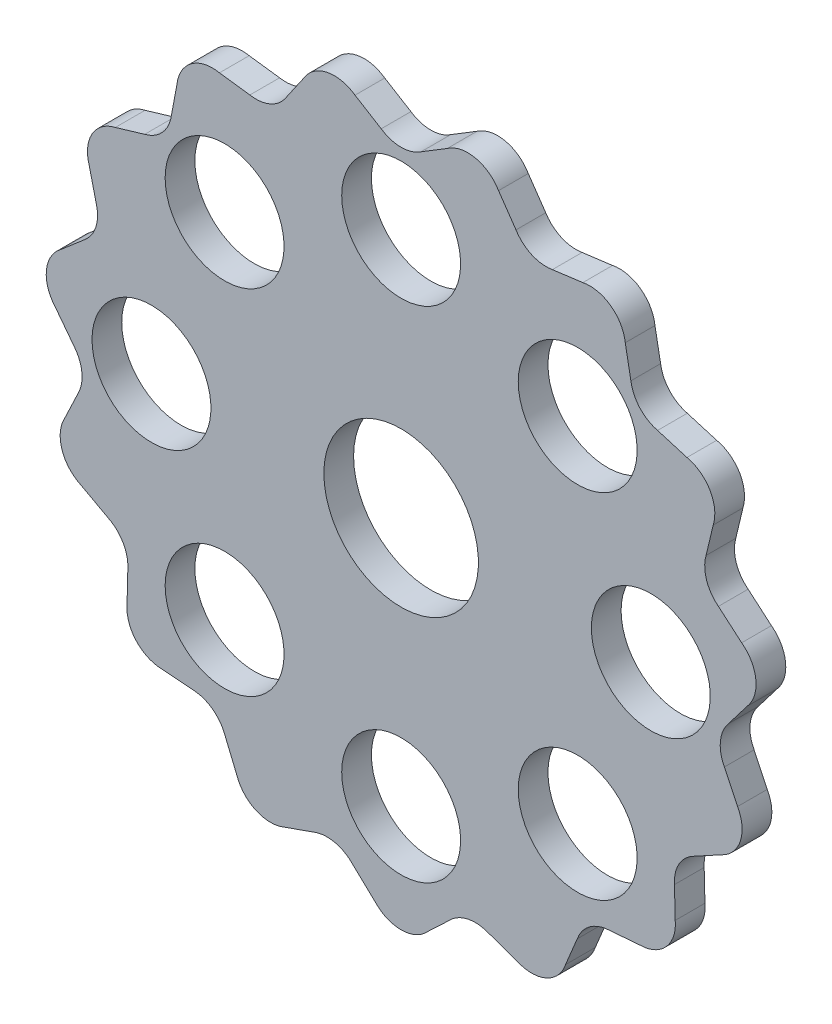
SolidWorks part; units mm, degrees
ref_plane "Plan de face" through (0, 0, 0) normal (0, 0, 1) x (1, 0, 0)
ref_plane "Plan de dessus" through (0, 0, 0) normal (0, 1, 0) x (1, 0, 0)
ref_plane "Plan de droite" through (0, 0, 0) normal (1, 0, 0) x (0, 0, -1)
sketch "Esquisse1" plane through (0, 0, 0) normal (0, 0, 1) x (1, 0, 0)
  line L0 (0, 0) -> (0, 70.8269) construction
  line L1 (0, 0) -> (-16.4135, 77.2197) construction
  line L2 (0, 0) -> (12.0589, 56.7326) construction
  line L3 (-3.3535, 55.0246) -> (3.3535, 55.0246) construction
  line L4 (0, 0) -> (-11.2473, 52.9146) construction
  line L5 (0, 0) -> (12.0589, 56.7326) construction
  line L6 (-11.2272, 52.82) -> (0, 0) construction
  line L7 (0, 0) -> (11.2272, 52.82) construction
  line L8 (-11.2272, 52.82) -> (11.2272, 52.82) construction
  line L9 (-7.7561, 57.7139) -> (7.7561, 57.7139) construction
  line L10 (-7.7561, 57.7139) -> (-3.3535, 55.0246)
  line L11 (3.3535, 55.0246) -> (7.7561, 57.7139)
  line L12 (0, 0) -> (17.0982, 80.4405) construction
  line L13 (16.3889, 55.879) -> (19.317, 51.6315)
  line L14 (25.4441, 48.9035) -> (30.5599, 49.5696)
  line L15 (37.7, 44.382) -> (38.6474, 39.3108)
  line L16 (43.1352, 34.3266) -> (48.0796, 32.8543)
  line L17 (52.4925, 25.211) -> (51.2953, 20.1929)
  line L18 (53.3678, 13.8142) -> (57.286, 10.4581)
  line L19 (58.2085, 1.6808) -> (55.0737, -2.4166)
  line L20 (54.3727, -9.0867) -> (56.5871, -13.7463)
  line L21 (53.8598, -22.14) -> (49.3295, -24.6081)
  line L22 (45.976, -30.4165) -> (46.1037, -35.5739)
  line L23 (40.1982, -42.1327) -> (35.0557, -42.5447)
  line L24 (29.6297, -46.487) -> (27.6486, -51.2505)
  line L25 (19.586, -54.8402) -> (14.7204, -53.125)
  line L26 (8.1601, -54.5194) -> (4.4128, -58.0653)
  line L27 (-4.4128, -58.0653) -> (-8.1601, -54.5194)
  line L28 (-14.7204, -53.125) -> (-19.586, -54.8402)
  line L29 (-27.6486, -51.2505) -> (-29.6297, -46.487)
  line L30 (-35.0557, -42.5447) -> (-40.1982, -42.1327)
  line L31 (-46.1037, -35.5739) -> (-45.976, -30.4165)
  line L32 (-49.3295, -24.6081) -> (-53.8598, -22.14)
  line L33 (-56.5871, -13.7463) -> (-54.3727, -9.0867)
  line L34 (-55.0737, -2.4166) -> (-58.2085, 1.6808)
  line L35 (-57.286, 10.4581) -> (-53.3678, 13.8142)
  line L36 (-51.2953, 20.1929) -> (-52.4925, 25.211)
  line L37 (-48.0796, 32.8543) -> (-43.1352, 34.3266)
  line L38 (-38.6474, 39.3108) -> (-37.7, 44.382)
  line L39 (-30.5599, 49.5696) -> (-25.4441, 48.9035)
  line L40 (-19.317, 51.6315) -> (-16.3889, 55.879)
  circle A4 centre (0, 0) radius 58 construction
  arc A5 (-3.3535, 55.0246) -> (3.3535, 55.0246) centre (0, 60) ccw
  arc A6 (12.4747, 58.6889) -> (7.7561, 57.7139) centre (11.2272, 52.82) ccw
  arc A8 (-12.4747, 58.6889) -> (-7.7561, 57.7139) centre (-11.2272, 52.82) cw
  arc A9 (12.4747, 58.6889) -> (16.3889, 55.879) centre (11.2272, 52.82) cw
  arc A10 (19.317, 51.6315) -> (25.4441, 48.9035) centre (24.4042, 54.8127) ccw
  arc A11 (35.2671, 48.541) -> (30.5599, 49.5696) centre (31.7404, 43.6869) ccw
  arc A12 (35.2671, 48.541) -> (37.7, 44.382) centre (31.7404, 43.6869) cw
  arc A13 (38.6474, 39.3108) -> (43.1352, 34.3266) centre (44.5887, 40.1478) ccw
  arc A14 (51.9615, 30) -> (48.0796, 32.8543) centre (46.7654, 27) ccw
  arc A15 (51.9615, 30) -> (52.4925, 25.211) centre (46.7654, 27) cw
  arc A16 (51.2953, 20.1929) -> (53.3678, 13.8142) centre (57.0634, 18.541) ccw
  arc A17 (59.6713, 6.2717) -> (57.286, 10.4581) centre (53.7042, 5.6445) ccw
  arc A18 (59.6713, 6.2717) -> (58.2085, 1.6808) centre (53.7042, 5.6445) cw
  arc A19 (55.0737, -2.4166) -> (54.3727, -9.0867) centre (59.6713, -6.2717) ccw
  arc A20 (57.0634, -18.541) -> (56.5871, -13.7463) centre (51.3571, -16.6869) ccw
  arc A21 (57.0634, -18.541) -> (53.8598, -22.14) centre (51.3571, -16.6869) cw
  arc A22 (49.3295, -24.6081) -> (45.976, -30.4165) centre (51.9615, -30) ccw
  arc A23 (44.5887, -40.1478) -> (46.1037, -35.5739) centre (40.1298, -36.1331) ccw
  arc A24 (44.5887, -40.1478) -> (40.1982, -42.1327) centre (40.1298, -36.1331) cw
  arc A25 (35.0557, -42.5447) -> (29.6297, -46.487) centre (35.2671, -48.541) ccw
  arc A26 (24.4042, -54.8127) -> (27.6486, -51.2505) centre (21.9638, -49.3315) ccw
  arc A27 (24.4042, -54.8127) -> (19.586, -54.8402) centre (21.9638, -49.3315) cw
  arc A28 (14.7204, -53.125) -> (8.1601, -54.5194) centre (12.4747, -58.6889) ccw
  arc A29 (0, -60) -> (4.4128, -58.0653) centre (0, -54) ccw
  arc A30 (0, -60) -> (-4.4128, -58.0653) centre (0, -54) cw
  arc A31 (-8.1601, -54.5194) -> (-14.7204, -53.125) centre (-12.4747, -58.6889) ccw
  arc A32 (-24.4042, -54.8127) -> (-19.586, -54.8402) centre (-21.9638, -49.3315) ccw
  arc A33 (-24.4042, -54.8127) -> (-27.6486, -51.2505) centre (-21.9638, -49.3315) cw
  arc A34 (-29.6297, -46.487) -> (-35.0557, -42.5447) centre (-35.2671, -48.541) ccw
  arc A35 (-44.5887, -40.1478) -> (-40.1982, -42.1327) centre (-40.1298, -36.1331) ccw
  arc A36 (-44.5887, -40.1478) -> (-46.1037, -35.5739) centre (-40.1298, -36.1331) cw
  arc A37 (-45.976, -30.4165) -> (-49.3295, -24.6081) centre (-51.9615, -30) ccw
  arc A38 (-57.0634, -18.541) -> (-53.8598, -22.14) centre (-51.3571, -16.6869) ccw
  arc A39 (-57.0634, -18.541) -> (-56.5871, -13.7463) centre (-51.3571, -16.6869) cw
  arc A40 (-54.3727, -9.0867) -> (-55.0737, -2.4166) centre (-59.6713, -6.2717) ccw
  arc A41 (-59.6713, 6.2717) -> (-58.2085, 1.6808) centre (-53.7042, 5.6445) ccw
  arc A42 (-59.6713, 6.2717) -> (-57.286, 10.4581) centre (-53.7042, 5.6445) cw
  arc A43 (-53.3678, 13.8142) -> (-51.2953, 20.1929) centre (-57.0634, 18.541) ccw
  arc A44 (-51.9615, 30) -> (-52.4925, 25.211) centre (-46.7654, 27) ccw
  arc A45 (-51.9615, 30) -> (-48.0796, 32.8543) centre (-46.7654, 27) cw
  arc A46 (-43.1352, 34.3266) -> (-38.6474, 39.3108) centre (-44.5887, 40.1478) ccw
  arc A47 (-35.2671, 48.541) -> (-37.7, 44.382) centre (-31.7404, 43.6869) ccw
  arc A48 (-35.2671, 48.541) -> (-30.5599, 49.5696) centre (-31.7404, 43.6869) cw
  arc A49 (-25.4441, 48.9035) -> (-19.317, 51.6315) centre (-24.4042, 54.8127) ccw
  arc A50 (-12.4747, 58.6889) -> (-16.3889, 55.879) centre (-11.2272, 52.82) ccw
  point P145 (0, 0)
  dimension "D2" = 6
  dimension "D3" = 24
  dimension "D5" = 6
  dimension "D7" = 60
  dimension "D8" = 54
  dimension "D11" = 15
  dimension "D14" = 116
  dimension "D4" = 6
  dimension "D6" = 12
  dimension "D10" = 12
  dimension "D9" = 12
extrude "Boss.-Extru.1" add sketch "Esquisse1" along normal blind 5
sketch "Esquisse2" plane through (0, 0, 0) normal (0, 0, -1) x (-1, 0, 0)
  line L0 (0, 0) -> (0, 51.5629) construction
  line L2 (0, 0) -> (0, -48.3315) construction
  line L5 (0, 0) -> (0, 46.1564) construction
  circle A0 centre (0, 0) radius 13
  circle A1 centre (0, 42) radius 10
  circle A6 centre (29.6985, 29.6985) radius 10
  circle A7 centre (42, 0) radius 10
  circle A8 centre (29.6985, -29.6985) radius 10
  circle A9 centre (0, -42) radius 10
  circle A10 centre (-29.6985, -29.6985) radius 10
  circle A11 centre (-42, 0) radius 10
  circle A12 centre (-29.6985, 29.6985) radius 10
  point P24 (0, 0)
  dimension "D1" = 26
  dimension "D2" = 20
  dimension "D3" = 8
  dimension "D12" = 42
extrude "Enlèv. mat.-Extru.1" cut sketch "Esquisse2" against normal through all
ref_point "Point1"
